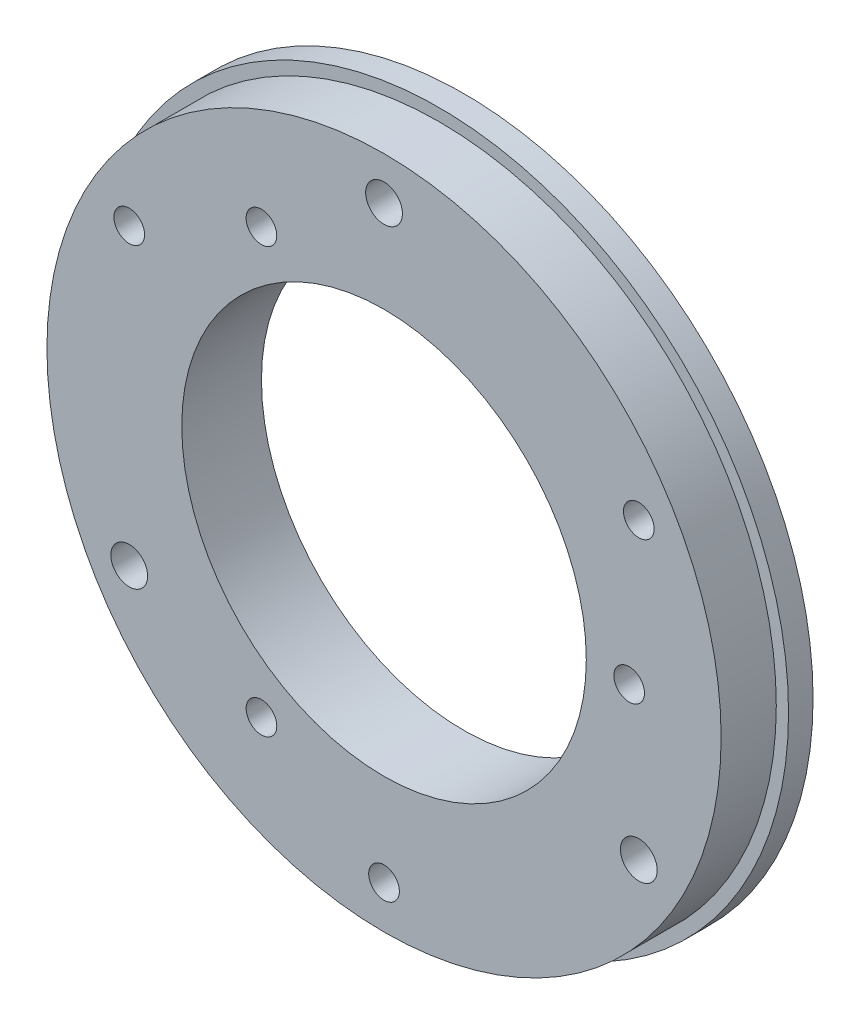
SolidWorks part; units mm, degrees
material "6061 Alloy"
ref_plane "Front Plane" through (0, 0, 0) normal (0, 0, 1) x (1, 0, 0)
ref_plane "Top Plane" through (0, 0, 0) normal (0, 1, 0) x (1, 0, 0)
ref_plane "Right Plane" through (0, 0, 0) normal (1, 0, 0) x (0, 0, -1)
sketch "Sketch1" plane through (0, 0, 0) normal (0, 0, 1) x (1, 0, 0)
  circle A0 centre (0, 0) radius 28.5
  circle A1 centre (0, 0) radius 19.5
  dimension "D1" = 57
  dimension "D2" = 39
extrude "Boss-Extrude1" add sketch "Sketch1" along normal blind 2
sketch "Sketch2" plane through (0, 0, 2) normal (0, 0, 1) x (1, 0, 0)
  circle A0 centre (0, 0) radius 27.5
  circle A1 centre (0, 0) radius 19.5
  dimension "D1" = 55
  dimension "D2" = 39
extrude "Boss-Extrude2" add sketch "Sketch2" along normal blind 4.5
sketch "Sketch3" plane through (0, 0, 6.5) normal (0, 0, 1) x (1, 0, 0)
  line L0 (0, 0) -> (0, 24) construction
  circle A0 centre (0, 0) radius 24 construction
  circle A1 centre (0, 24) radius 1.25
  dimension "D1" = 48
  dimension "D2" = 2.5
extrude "Cut-Extrude1" cut sketch "Sketch3" against normal through all
pattern_circular "CirPattern1" count 6 over 360 about axis through (0, 0, 0) along (0, 0, 1) of "Cut-Extrude1"
sketch "Sketch5" plane through (0, 0, 0) normal (0, 0, -1) x (-1, 0, 0)
  line L0 (0, 18.5) -> (0, 16.5) construction
  circle A0 centre (0, 0) radius 20 construction
  circle A1 centre (0, 20) radius 1.5 construction
  circle A3 centre (0, 0) radius 19.5
  circle A4 centre (0, 0) radius 16.5
  dimension "D1" = 40
  dimension "D2" = 3
  dimension "D3" = 2
  dimension "D4" = 39
extrude "Boss-Extrude3" add sketch "Sketch5" against normal up to surface (6.5 mm away) up to face at (21.4096, 10.9175, 6.5)
sketch "Sketch6" plane through (0, 0, 0) normal (0, 0, -1) x (-1, 0, 0)
  line L0 (0, 24) -> (0, 0) construction
  line L1 (0, 0) -> (10, 17.3205) construction
  circle A0 centre (0, 0) radius 20 construction
  circle A1 centre (10, 17.3205) radius 1.25
  dimension "D1" = 40
  dimension "D3" = 2.5
  dimension "D2" = 30
extrude "Cut-Extrude2" cut sketch "Sketch6" against normal blind 10
pattern_circular "CirPattern2" count 3 over 360 about axis through (0, 0, 0) along (0, 0, 1) of "Cut-Extrude2"
sketch "Sketch8" plane through (0, 0, 0) normal (0, 0, -1) x (-1, 0, 0)
  circle A0 centre (0, 24) radius 3
  dimension "D1" = 6
extrude "Cut-Extrude4" cut sketch "Sketch8" against normal blind 3.5
pattern_circular "CirPattern4" count 3 over 360 about axis through (0, 0, 0) along (0, 0, 1) of "Cut-Extrude4"
sketch "Sketch9" plane through (0, 0, 3.5) normal (0, 0, -1) x (-1, 0, 0)
  circle A0 centre (0, 24) radius 1.5
  circle A1 centre (20.7846, -12) radius 1.5
  circle A2 centre (-20.7846, -12) radius 1.5
  point P10 (0, 0)
  dimension "D1" = 3
  dimension "D2" = 3
extrude "Cut-Extrude5" cut sketch "Sketch9" against normal through all
